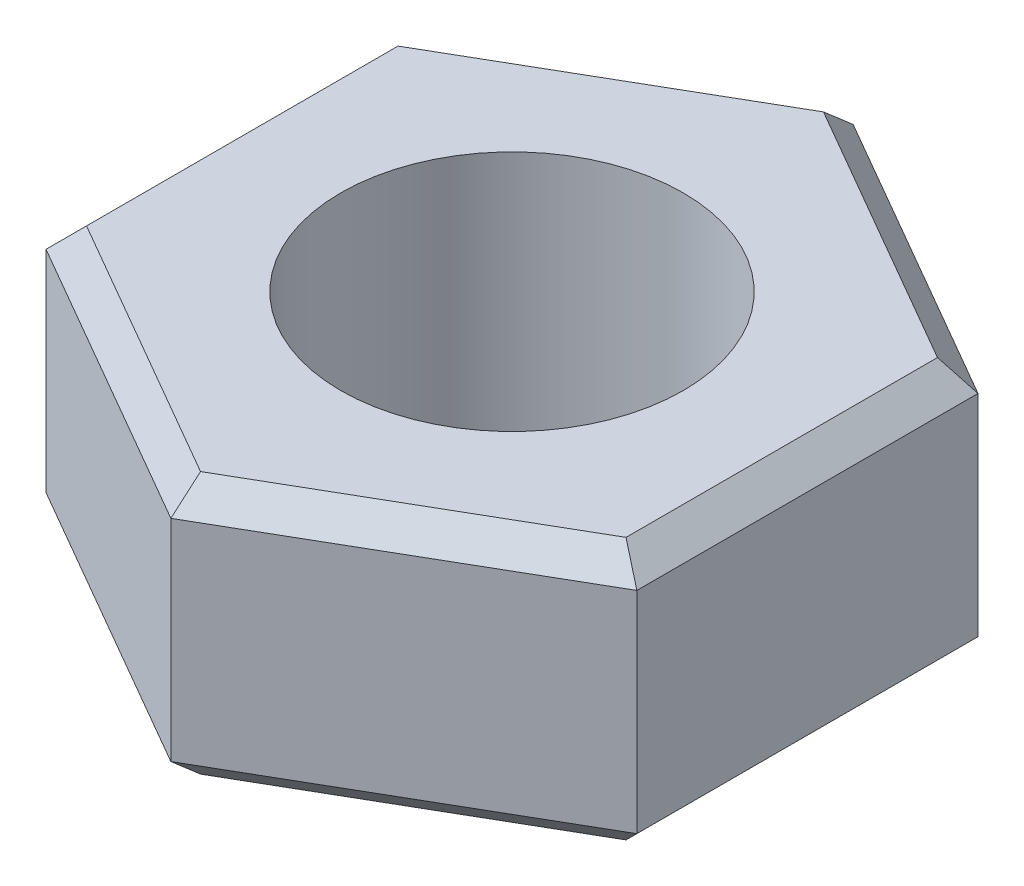
SolidWorks part; units mm, degrees
ref_plane "前视基准面" through (0, 0, 0) normal (0, 0, 1) x (1, 0, 0)
ref_plane "上视基准面" through (0, 0, 0) normal (0, 1, 0) x (1, 0, 0)
ref_plane "右视基准面" through (0, 0, 0) normal (1, 0, 0) x (0, 0, -1)
sketch "草图1" plane through (0, 0, 0) normal (0, 1, 0) x (1, 0, 0)
  line L1 (0, 3.9837) -> (-3.45, 1.9919)
  line L2 (-3.45, 1.9919) -> (-3.45, -1.9919)
  line L3 (-3.45, -1.9919) -> (0, -3.9837)
  line L4 (0, -3.9837) -> (3.45, -1.9919)
  line L5 (3.45, -1.9919) -> (3.45, 1.9919)
  line L6 (3.45, 1.9919) -> (0, 3.9837)
  circle A0 centre (0, 0) radius 3.45 construction
  circle A1 centre (0, 0) radius 2
  dimension "D2" = 4
  dimension "D1" = 6.9
extrude "凸台-拉伸1" add sketch "草图1" along normal blind 3.06
chamfer "倒角1" distance 0.3 angle 45 12 edges at (3.45, 3.06, 0) (1.725, 3.06, 2.9878) (-1.725, 3.06, 2.9878) (-3.45, 3.06, 0) (-1.725, 3.06, -2.9878) (1.725, 3.06, -2.9878) (-1.725, 0, -2.9878) (-3.45, 0, 0) (-1.725, 0, 2.9878) (1.725, 0, 2.9878) (3.45, 0, 0) (1.725, 0, -2.9878)
